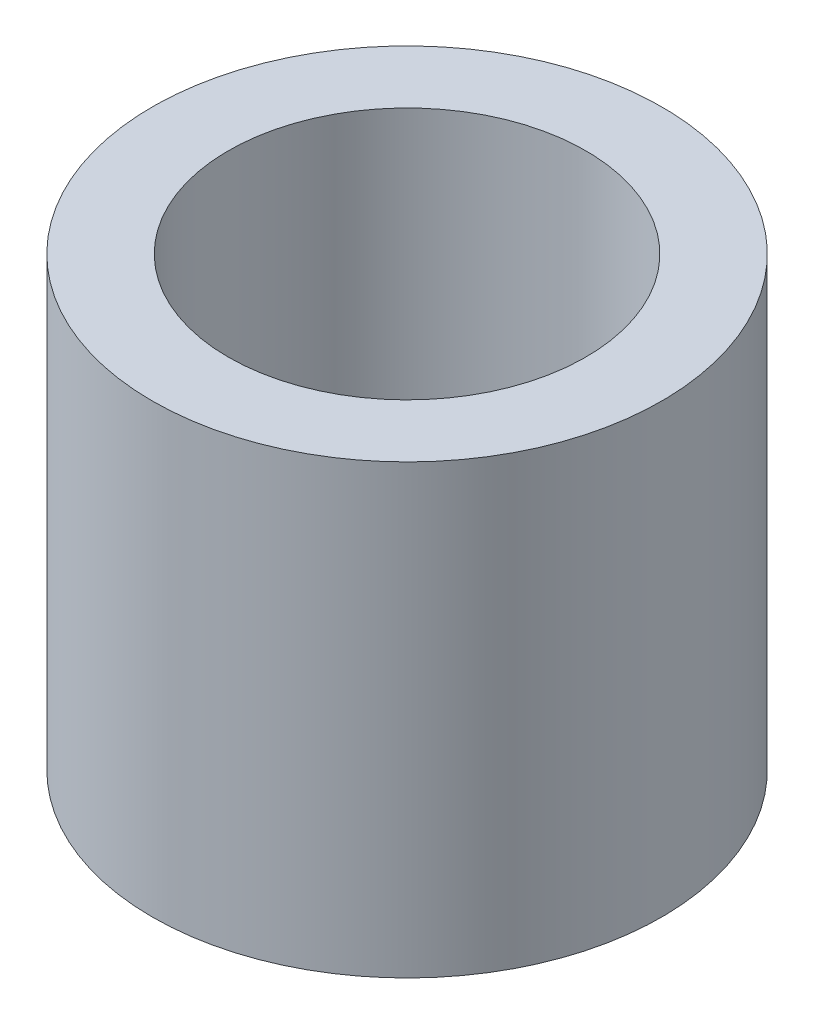
SolidWorks part; units mm, degrees
ref_plane "Front Plane" through (0, 0, 0) normal (0, 0, 1) x (1, 0, 0)
ref_plane "Top Plane" through (0, 0, 0) normal (0, 1, 0) x (1, 0, 0)
ref_plane "Right Plane" through (0, 0, 0) normal (1, 0, 0) x (0, 0, -1)
sketch "Sketch1" plane through (0, 0, 0) normal (0, 1, 0) x (1, 0, 0)
  circle A0 centre (0, 0) radius 5.7
  circle A1 centre (0, 0) radius 4
  dimension "D1" = 11.4
  dimension "D2" = 8
extrude "Boss-Extrude1" add sketch "Sketch1" along normal blind 10
